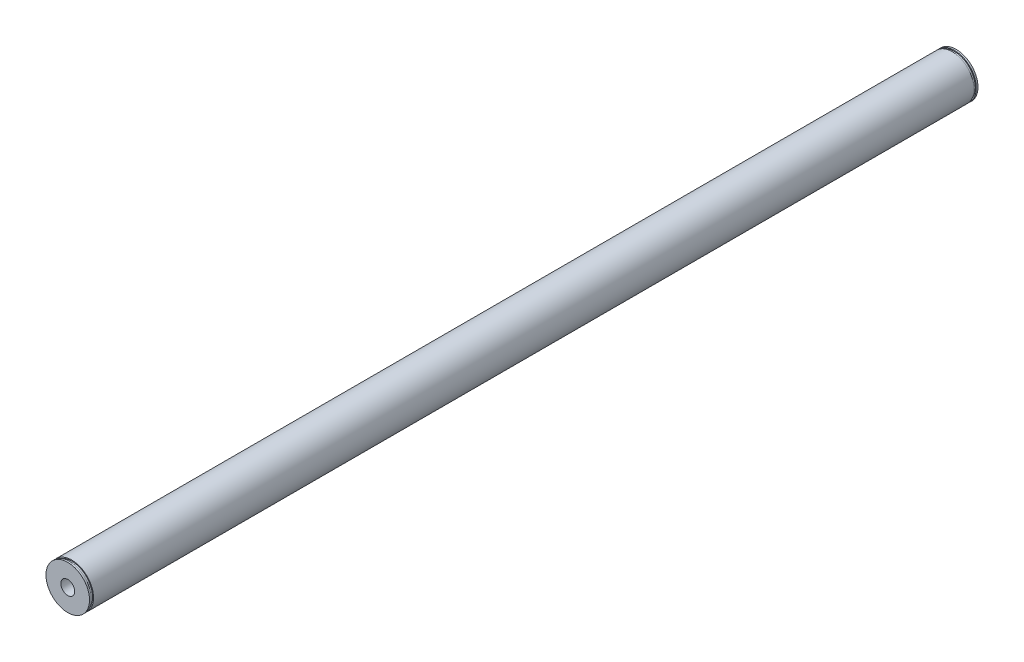
SolidWorks part; units mm, degrees
material "AISI 304"
ref_plane "Piano frontale" through (0, 0, 0) normal (0, 0, 1) x (1, 0, 0)
ref_plane "Piano superiore" through (0, 0, 0) normal (0, 1, 0) x (1, 0, 0)
ref_plane "Piano destro" through (0, 0, 0) normal (1, 0, 0) x (0, 0, -1)
sketch "Schizzo1" plane through (0, 0, 0) normal (0, 0, 1) x (1, 0, 0)
  circle A0 centre (0, 0) radius 12.5
  dimension "D1" = 25
extrude "Estrusione1" add sketch "Schizzo1" along normal blind 510
sketch "Schizzo2" plane through (0, 0, 510) normal (0, 0, 1) x (1, 0, 0)
  circle A0 centre (0, 0) radius 4
  dimension "D1" = 8
extrude "Taglio-Estrusione1" cut sketch "Schizzo2" against normal blind 30
sketch "Schizzo3" plane through (0, 0, 0) normal (0, 0, -1) x (-1, 0, 0)
  circle A0 centre (0, 0) radius 4 construction
  circle A1 centre (0, 0) radius 4
extrude "Taglio-Estrusione2" cut sketch "Schizzo3" against normal blind 30
ref_plane "Piano1" through (0, 0, 508.35) normal (0, 0, 1) x (1, 0, 0)
sketch "Schizzo5" plane through (0, 0, 0) normal (1, 0, 0) x (0, 0, -1)
  line L0 (-508.35, 13.75) -> (-508.35, -13.75) construction
  line L1 (-509, 12.5) -> (-507.7, 12.5)
  line L2 (-509, 12.5) -> (-509, 11.95)
  line L3 (-509, 11.95) -> (-507.7, 11.95)
  line L4 (-507.7, 12.5) -> (-507.7, 11.95)
  line L5 (0, 12.5) -> (-510, 12.5) construction
  line L6 (-255, 35.5345) -> (-255, -29.716) construction
  line L7 (-510, 12.5) -> (-510, -12.5) construction
  line L8 (-2.3, 12.5) -> (-2.3, 11.95)
  line L9 (-1, 11.95) -> (-2.3, 11.95)
  line L10 (-1, 12.5) -> (-1, 11.95)
  line L11 (-1, 12.5) -> (-2.3, 12.5)
  dimension "D1" = 0.65
  dimension "D2" = 1.3
  dimension "D3" = 0.55
  dimension "D4" = 255
revolve "Taglia-Rivoluzione1" cut sketch "Schizzo5" angle 360 about axis through (0, 0, 510) along (0, 0, -1)
